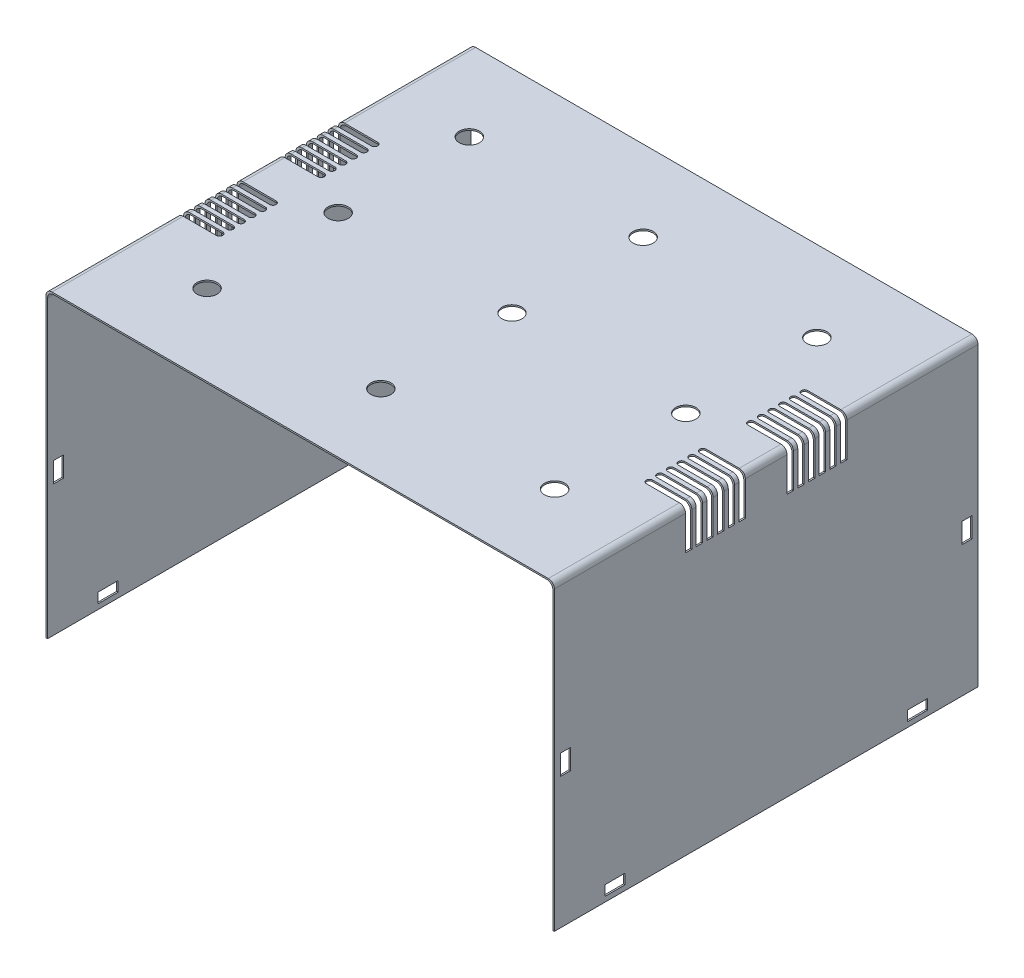
SolidWorks part; units mm, degrees
ref_plane "Alzado" through (0, 0, 0) normal (0, 0, 1) x (1, 0, 0)
ref_plane "Planta" through (0, 0, 0) normal (0, 1, 0) x (1, 0, 0)
ref_plane "Vista lateral" through (0, 0, 0) normal (1, 0, 0) x (0, 0, -1)
sketch "Croquis1" plane through (0, 0, 0) normal (0, 0, 1) x (1, 0, 0)
  line L0 (-126, 0) -> (-126, 147)
  line L1 (-123, 150) -> (123, 150)
  line L2 (126, 147) -> (126, 0)
  line L3 (-126, 0) -> (-125.25, 0)
  line L4 (-125.25, 0) -> (-125.25, 146.25)
  line L5 (-122.25, 149.25) -> (122.25, 149.25)
  line L6 (125.25, 146.25) -> (125.25, 0)
  line L7 (125.25, 0) -> (126, 0)
  arc A0 (-126, 147) -> (-123, 150) centre (-123, 147) cw
  arc A1 (-125.25, 146.25) -> (-122.25, 149.25) centre (-122.25, 146.25) cw
  arc A2 (123, 150) -> (126, 147) centre (123, 147) cw
  arc A3 (122.25, 149.25) -> (125.25, 146.25) centre (122.25, 146.25) cw
  point P3 (0, 150)
  point P12 (-126, 150)
  point P17 (126, 150)
  dimension "D7" = 3
  dimension "D1" = 252
  dimension "D2" = 150
  dimension "D3" = 150
  dimension "D4" = 0.75
  dimension "D5" = 0.75
  dimension "D6" = 0.75
extrude "Saliente-Extruir1" add sketch "Croquis1" against normal blind 210
sketch "Croquis4" plane through (0, 150, 0) normal (0, 1, 0) x (1, 0, 0)
  line L0 (-106.575, 94.65) -> (-128.425, 94.65)
  line L1 (-128.425, 91.5) -> (-106.575, 91.5)
  line L2 (-106.575, 145) -> (-128.425, 145)
  line L4 (-128.425, 141.85) -> (-106.575, 141.85)
  line L5 (-106.575, 89.35) -> (-128.425, 89.35)
  line L6 (-128.425, 86.2) -> (-106.575, 86.2)
  line L7 (-106.575, 84.05) -> (-128.425, 84.05)
  line L8 (-128.425, 80.9) -> (-106.575, 80.9)
  line L9 (-106.575, 78.75) -> (-128.425, 78.75)
  line L10 (-128.425, 75.6) -> (-106.575, 75.6)
  line L11 (-106.575, 73.45) -> (-128.425, 73.45)
  line L12 (0, 0) -> (0, 210) construction
  line L13 (123, 210) -> (-123, 210) construction
  line L14 (-128.425, 136.55) -> (-106.575, 136.55)
  line L15 (-106.575, 139.7) -> (-128.425, 139.7)
  line L16 (-128.425, 131.25) -> (-106.575, 131.25)
  line L17 (-106.575, 134.4) -> (-128.425, 134.4)
  line L18 (-128.425, 125.95) -> (-106.575, 125.95)
  line L19 (-106.575, 129.1) -> (-128.425, 129.1)
  line L20 (-128.425, 120.65) -> (-106.575, 120.65)
  line L21 (-106.575, 123.8) -> (-128.425, 123.8)
  line L22 (-128.425, 115.35) -> (-106.575, 115.35)
  line L23 (-106.575, 118.5) -> (-128.425, 118.5)
  line L24 (-128.425, 70.3) -> (-106.575, 70.3)
  line L25 (-106.575, 68.15) -> (-128.425, 68.15)
  line L26 (-128.425, 65) -> (-106.575, 65)
  line L27 (106.575, 118.5) -> (128.425, 118.5)
  line L28 (128.425, 115.35) -> (106.575, 115.35)
  line L29 (106.575, 123.8) -> (128.425, 123.8)
  line L30 (128.425, 120.65) -> (106.575, 120.65)
  line L31 (106.575, 129.1) -> (128.425, 129.1)
  line L32 (128.425, 125.95) -> (106.575, 125.95)
  line L33 (106.575, 134.4) -> (128.425, 134.4)
  line L34 (128.425, 131.25) -> (106.575, 131.25)
  line L35 (106.575, 139.7) -> (128.425, 139.7)
  line L36 (128.425, 136.55) -> (106.575, 136.55)
  line L37 (106.575, 145) -> (128.425, 145)
  line L38 (128.425, 141.85) -> (106.575, 141.85)
  line L39 (128.425, 65) -> (106.575, 65)
  line L40 (106.575, 68.15) -> (128.425, 68.15)
  line L41 (128.425, 70.3) -> (106.575, 70.3)
  line L42 (106.575, 73.45) -> (128.425, 73.45)
  line L43 (128.425, 75.6) -> (106.575, 75.6)
  line L44 (106.575, 78.75) -> (128.425, 78.75)
  line L45 (128.425, 80.9) -> (106.575, 80.9)
  line L46 (106.575, 84.05) -> (128.425, 84.05)
  line L47 (128.425, 86.2) -> (106.575, 86.2)
  line L48 (106.575, 89.35) -> (128.425, 89.35)
  line L49 (128.425, 91.5) -> (106.575, 91.5)
  line L50 (106.575, 94.65) -> (128.425, 94.65)
  line L52 (123, 0) -> (-123, 0) construction
  arc A0 (-106.575, 141.85) -> (-106.575, 145) centre (-106.575, 143.425) ccw
  arc A1 (-128.425, 145) -> (-128.425, 141.85) centre (-128.425, 143.425) ccw
  arc A2 (-128.425, 139.7) -> (-128.425, 136.55) centre (-128.425, 138.125) ccw
  arc A3 (-106.575, 136.55) -> (-106.575, 139.7) centre (-106.575, 138.125) ccw
  arc A4 (-128.425, 134.4) -> (-128.425, 131.25) centre (-128.425, 132.825) ccw
  arc A5 (-106.575, 131.25) -> (-106.575, 134.4) centre (-106.575, 132.825) ccw
  arc A6 (-128.425, 129.1) -> (-128.425, 125.95) centre (-128.425, 127.525) ccw
  arc A7 (-106.575, 125.95) -> (-106.575, 129.1) centre (-106.575, 127.525) ccw
  arc A8 (-128.425, 123.8) -> (-128.425, 120.65) centre (-128.425, 122.225) ccw
  arc A9 (-106.575, 120.65) -> (-106.575, 123.8) centre (-106.575, 122.225) ccw
  arc A10 (-128.425, 118.5) -> (-128.425, 115.35) centre (-128.425, 116.925) ccw
  arc A11 (-106.575, 115.35) -> (-106.575, 118.5) centre (-106.575, 116.925) ccw
  arc A12 (-106.575, 91.5) -> (-106.575, 94.65) centre (-106.575, 93.075) ccw
  arc A13 (-128.425, 94.65) -> (-128.425, 91.5) centre (-128.425, 93.075) ccw
  arc A14 (-128.425, 89.35) -> (-128.425, 86.2) centre (-128.425, 87.775) ccw
  arc A15 (-106.575, 86.2) -> (-106.575, 89.35) centre (-106.575, 87.775) ccw
  arc A16 (-128.425, 84.05) -> (-128.425, 80.9) centre (-128.425, 82.475) ccw
  arc A17 (-106.575, 80.9) -> (-106.575, 84.05) centre (-106.575, 82.475) ccw
  arc A18 (-128.425, 78.75) -> (-128.425, 75.6) centre (-128.425, 77.175) ccw
  arc A19 (-106.575, 75.6) -> (-106.575, 78.75) centre (-106.575, 77.175) ccw
  arc A20 (-128.425, 73.45) -> (-128.425, 70.3) centre (-128.425, 71.875) ccw
  arc A21 (-106.575, 70.3) -> (-106.575, 73.45) centre (-106.575, 71.875) ccw
  arc A22 (-128.425, 68.15) -> (-128.425, 65) centre (-128.425, 66.575) ccw
  arc A23 (-106.575, 65) -> (-106.575, 68.15) centre (-106.575, 66.575) ccw
  arc A24 (128.425, 118.5) -> (128.425, 115.35) centre (128.425, 116.925) cw
  arc A25 (106.575, 115.35) -> (106.575, 118.5) centre (106.575, 116.925) cw
  arc A26 (128.425, 123.8) -> (128.425, 120.65) centre (128.425, 122.225) cw
  arc A27 (106.575, 120.65) -> (106.575, 123.8) centre (106.575, 122.225) cw
  arc A28 (128.425, 129.1) -> (128.425, 125.95) centre (128.425, 127.525) cw
  arc A29 (106.575, 125.95) -> (106.575, 129.1) centre (106.575, 127.525) cw
  arc A30 (128.425, 134.4) -> (128.425, 131.25) centre (128.425, 132.825) cw
  arc A31 (106.575, 131.25) -> (106.575, 134.4) centre (106.575, 132.825) cw
  arc A32 (128.425, 139.7) -> (128.425, 136.55) centre (128.425, 138.125) cw
  arc A33 (106.575, 136.55) -> (106.575, 139.7) centre (106.575, 138.125) cw
  arc A34 (106.575, 141.85) -> (106.575, 145) centre (106.575, 143.425) cw
  arc A35 (128.425, 145) -> (128.425, 141.85) centre (128.425, 143.425) cw
  arc A36 (106.575, 65) -> (106.575, 68.15) centre (106.575, 66.575) cw
  arc A37 (128.425, 68.15) -> (128.425, 65) centre (128.425, 66.575) cw
  arc A38 (106.575, 70.3) -> (106.575, 73.45) centre (106.575, 71.875) cw
  arc A39 (128.425, 73.45) -> (128.425, 70.3) centre (128.425, 71.875) cw
  arc A40 (106.575, 75.6) -> (106.575, 78.75) centre (106.575, 77.175) cw
  arc A41 (128.425, 78.75) -> (128.425, 75.6) centre (128.425, 77.175) cw
  arc A42 (106.575, 80.9) -> (106.575, 84.05) centre (106.575, 82.475) cw
  arc A43 (128.425, 84.05) -> (128.425, 80.9) centre (128.425, 82.475) cw
  arc A44 (106.575, 86.2) -> (106.575, 89.35) centre (106.575, 87.775) cw
  arc A45 (128.425, 89.35) -> (128.425, 86.2) centre (128.425, 87.775) cw
  arc A46 (106.575, 91.5) -> (106.575, 94.65) centre (106.575, 93.075) cw
  arc A47 (128.425, 94.65) -> (128.425, 91.5) centre (128.425, 93.075) cw
  point P8 (-130, 143.425)
  point P9 (-105, 143.425)
  dimension "D1" = 25
  dimension "D2" = 3.15
  dimension "D4" = 65
  dimension "D5" = 65
  dimension "D6" = 3.15
  dimension "D8" = 29.65
  dimension "D3" = 6
  dimension "D7" = 6
extrude "Cortar-Extruir3" cut sketch "Croquis4" against normal blind 20
sketch "Croquis5" plane through (126, 0, 0) normal (1, 0, 0) x (0, 0, -1)
  line L0 (210, 0) -> (0, 0) construction
  line L1 (25, 7.5) -> (35, 7.5)
  line L2 (25, 7.5) -> (25, 2.5)
  line L3 (25, 2.5) -> (35, 2.5)
  line L4 (35, 7.5) -> (35, 2.5)
  line L5 (175, 7.5) -> (185, 7.5)
  line L6 (175, 7.5) -> (175, 2.5)
  line L7 (175, 2.5) -> (185, 2.5)
  line L8 (185, 7.5) -> (185, 2.5)
  line L9 (202, 75) -> (207, 75)
  line L10 (202, 75) -> (202, 65)
  line L11 (202, 65) -> (207, 65)
  line L12 (207, 75) -> (207, 65)
  line L13 (3, 75) -> (8, 75)
  line L14 (3, 75) -> (3, 65)
  line L15 (3, 65) -> (8, 65)
  line L16 (8, 75) -> (8, 65)
  line L17 (0, 0) -> (0, 147) construction
  line L18 (210, 0) -> (210, 147) construction
  dimension "D1" = 10
  dimension "D2" = 5
  dimension "D3" = 2.5
  dimension "D4" = 2.5
  dimension "D5" = 25
  dimension "D6" = 25
  dimension "D7" = 65
  dimension "D8" = 65
  dimension "D9" = 3
  dimension "D10" = 3
extrude "Cortar-Extruir4" cut sketch "Croquis5" against normal blind 271
sketch "Croquis6" plane through (0, 150, 0) normal (0, 1, 0) x (1, 0, 0)
  line L0 (0, 0) -> (0, 210) construction
  line L1 (123, 210) -> (-123, 210) construction
  line L2 (-86.15, 210) -> (-86.15, 0) construction
  line L3 (123, 0) -> (-123, 0) construction
  line L4 (86.15, 210) -> (86.15, 0) construction
  line L5 (-123, 105) -> (123, 105) construction
  line L6 (-123, 115.35) -> (-123, 94.65) construction
  line L7 (123, 115.35) -> (123, 94.65) construction
  circle A0 centre (-86.15, 105) radius 5
  circle A1 centre (0, 105) radius 5
  circle A2 centre (86.15, 105) radius 5
  circle A3 centre (-86.15, 170) radius 5
  circle A4 centre (-86.15, 40) radius 5
  circle A5 centre (0, 170) radius 5
  circle A6 centre (86.15, 170) radius 5
  circle A7 centre (86.15, 40) radius 5
  circle A8 centre (0, 40) radius 5
  dimension "D3" = 10
  dimension "D1" = 86.15
  dimension "D2" = 86.15
  dimension "D4" = 65
  dimension "D5" = 65
extrude "Cortar-Extruir5" cut sketch "Croquis6" against normal blind 10
